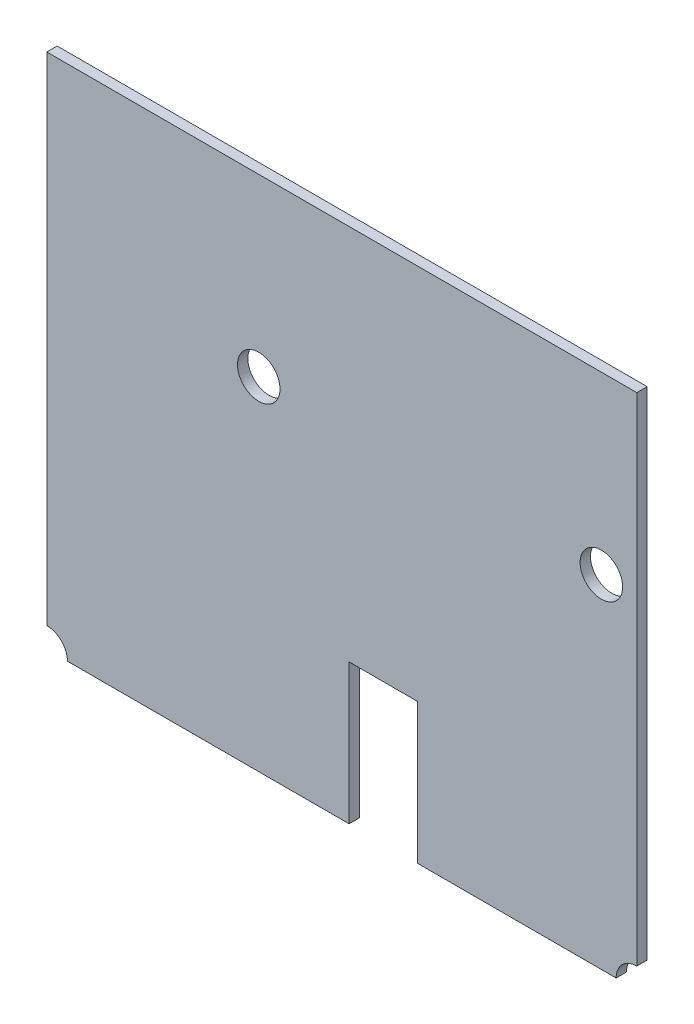
SolidWorks part; units mm, degrees
ref_plane "Спереди" through (0, 0, 0) normal (0, 0, 1) x (1, 0, 0)
ref_plane "Сверху" through (0, 0, 0) normal (0, 1, 0) x (1, 0, 0)
ref_plane "Справа" through (0, 0, 0) normal (1, 0, 0) x (0, 0, -1)
sketch "Model" plane through (0, 0, 0) normal (0, 0, 1) x (1, 0, 0)
  line L0 (2635.236, -2604.3598) -> (2641.8578, -2604.3598)
  line L1 (2608.0305, -2617.9043) -> (2635.236, -2617.9043)
  line L2 (2661.0289, -2617.9043) -> (2641.8578, -2617.9043)
  line L135 (2606.04, -2567.94) -> (2606.04, -2615.9138)
  line L147 (2635.236, -2617.9043) -> (2635.236, -2604.3598)
  line L185 (2641.8578, -2604.3598) -> (2641.8578, -2617.9043)
  line L197 (2663.0274, -2615.9058) -> (2663.0274, -2567.94)
  line L198 (2663.0274, -2567.94) -> (2606.04, -2567.94)
  arc A0 (2606.04, -2615.9138) -> (2608.0305, -2617.9043) centre (2606.04, -2617.9043) cw
  arc A1 (2663.0274, -2615.9058) -> (2661.0289, -2617.9043) centre (2663.0274, -2617.9043) ccw
  circle A2 centre (2626.5073, -2584.8749) radius 2.054
  circle A3 centre (2659.6026, -2584.8795) radius 2.054
extrude "Бобышка-Вытянуть1" add sketch "Model" along normal blind 1
